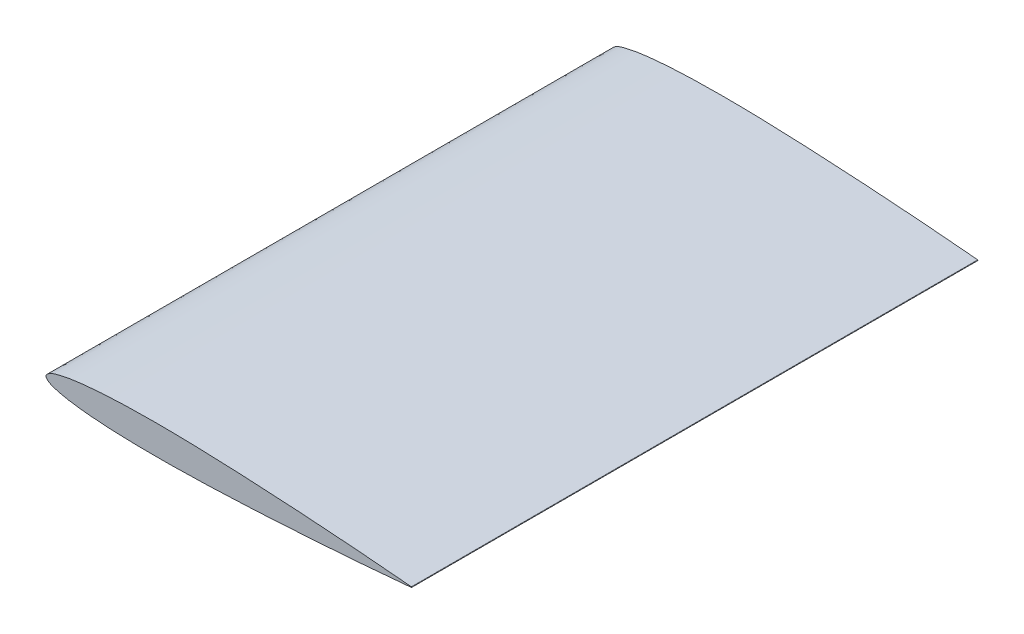
SolidWorks part; units mm, degrees
material "Manual Density from Real Component Stab Orizz. Ext Legno"
ref_plane "Piano frontale" through (0, 0, 0) normal (0, 0, 1) x (1, 0, 0)
ref_plane "Piano superiore" through (0, 0, 0) normal (0, 1, 0) x (1, 0, 0)
ref_plane "Piano destro" through (0, 0, 0) normal (1, 0, 0) x (0, 0, -1)
curve "Curva1"
  spline degree 3 poles (100, 0.084, 0) (98.3335, 0.2367, 0) (95.0012, 0.5422, 0) (88.3356, 1.1109, 0) (80.0033, 1.7636, 0) (70.003, 2.4579, 0) (60.0031, 3.0617, 0) (50.003, 3.5521, 0) (40.0026, 3.9029, 0) (31.667, 4.0253, 0) (24.9992, 3.9769, 0) (19.9978, 3.845, 0) (14.9934, 3.5925, 0) (10.8272, 3.2377, 0) (7.4891, 2.814, 0) (4.9936, 2.4037, 0) (2.8496, 1.8679, 0) (1.1654, 1.321, 0) (-0.6646, 0, 0) (1.1654, -1.321, 0) (2.8496, -1.8679, 0) (4.9936, -2.4037, 0) (7.4891, -2.814, 0) (10.8272, -3.2377, 0) (14.9934, -3.5925, 0) (19.9978, -3.845, 0) (24.9992, -3.9769, 0) (31.667, -4.0253, 0) (40.0026, -3.9029, 0) (50.003, -3.5521, 0) (60.0031, -3.0617, 0) (70.003, -2.4579, 0) (80.0033, -1.7636, 0) (88.3356, -1.1109, 0) (95.0012, -0.5422, 0) (98.3335, -0.2367, 0) (100, -0.084, 0) knots 0 0 0 0 0.024876 0.049742 0.099443 0.149112 0.198751 0.248359 0.297937 0.347491 0.372267 0.397051 0.421859 0.446731 0.45922 0.471791 0.48456 0.491195 0.5 0.508805 0.51544 0.528209 0.54078 0.553269 0.578141 0.602949 0.627733 0.652509 0.702063 0.751641 0.801249 0.850888 0.900557 0.950258 0.975124 1 1 1 1
sketch "Schizzo1" plane through (0, 0, 0) normal (0, 0, 1) x (1, 0, 0)
  line L0 (70, 2.443) -> (70, -2.443) construction
  arc A1 (70, -2.443) -> (70, 2.443) centre (70, 0) cw
  spline S0 degree 3 poles (905.2539, 3897.2705) (397.5402, -70.8596) (246.6176, -12.3941) (88.3356, 1.1109) (80.0033, 1.7636) (70.003, 2.4579) (60.0031, 3.0617) (50.003, 3.5521) (40.0026, 3.9029) (31.667, 4.0253) (24.9992, 3.9769) (19.9978, 3.845) (14.9934, 3.5925) (10.8272, 3.2377) (7.4891, 2.814) (4.9936, 2.4037) (2.8496, 1.8679) (1.1654, 1.321) (-0.6646, 0) (1.1654, -1.321) (2.8496, -1.8679) (4.9936, -2.4037) (7.4891, -2.814) (10.8272, -3.2377) (14.9934, -3.5925) (19.9978, -3.845) (24.9992, -3.9769) (31.667, -4.0253) (40.0026, -3.9029) (50.003, -3.5521) (60.0031, -3.0617) (70.003, -2.4579) (80.0033, -1.7636) (88.3356, -1.1109) (246.6156, 12.3939) (397.5363, 70.8581) (905.2338, -3897.1134) knots -2.261938 -2.261938 -2.261938 -2.261938 0.024876 0.049742 0.099443 0.149112 0.198751 0.248359 0.297937 0.347491 0.372267 0.397051 0.421859 0.446731 0.45922 0.471791 0.48456 0.491195 0.5 0.508805 0.51544 0.528209 0.54078 0.553269 0.578141 0.602949 0.627733 0.652509 0.702063 0.751641 0.801249 0.850888 0.900557 0.950258 0.975124 3.261907 3.261907 3.261907 3.261907 only from (100, 0.084) to (100, -0.084) construction
  spline S1 degree 3 poles (70, 2.443) (66.6677, 2.6593) (60.0031, 3.0617) (50.003, 3.5521) (40.0026, 3.9029) (31.667, 4.0253) (24.9992, 3.9769) (19.9978, 3.845) (14.9934, 3.5925) (10.8272, 3.2377) (7.4891, 2.814) (4.9936, 2.4037) (2.8496, 1.8679) (1.1654, 1.321) (-0.6646, 0) (1.1654, -1.321) (2.8496, -1.8679) (4.9936, -2.4037) (7.4891, -2.814) (10.8272, -3.2377) (14.9934, -3.5925) (19.9978, -3.845) (24.9992, -3.9769) (31.667, -4.0253) (40.0026, -3.9029) (50.003, -3.5521) (60.0031, -3.0617) (66.6677, -2.6593) (70, -2.443) knots 0.149112 0.149112 0.149112 0.149112 0.198751 0.248359 0.297937 0.347491 0.372267 0.397051 0.421859 0.446731 0.45922 0.471791 0.48456 0.491195 0.5 0.508805 0.51544 0.528209 0.54078 0.553269 0.578141 0.602949 0.627733 0.652509 0.702063 0.751641 0.801249 0.850888 0.850888 0.850888 0.850888
  dimension "D1" = 4.886
extrude "CorpoFoam" add sketch "Schizzo1" along normal blind 132
sketch "Schizzo7" plane through (0, 0, 132) normal (0, 0, 1) x (1, 0, 0)
  arc A0 (100, 0.084) -> (100, -0.084) centre (100, 0) cw
  spline S0 degree 3 poles (905.2539, 3897.2705) (397.5402, -70.8596) (246.6176, -12.3941) (88.3356, 1.1109) (80.0033, 1.7636) (70.003, 2.4579) (60.0031, 3.0617) (50.003, 3.5521) (40.0026, 3.9029) (31.667, 4.0253) (24.9992, 3.9769) (19.9978, 3.845) (14.9934, 3.5925) (10.8272, 3.2377) (7.4891, 2.814) (4.9936, 2.4037) (2.8496, 1.8679) (1.1654, 1.321) (-0.6646, 0) (1.1654, -1.321) (2.8496, -1.8679) (4.9936, -2.4037) (7.4891, -2.814) (10.8272, -3.2377) (14.9934, -3.5925) (19.9978, -3.845) (24.9992, -3.9769) (31.667, -4.0253) (40.0026, -3.9029) (50.003, -3.5521) (60.0031, -3.0617) (70.003, -2.4579) (80.0033, -1.7636) (88.3356, -1.1109) (246.6156, 12.3939) (397.5363, 70.8581) (905.2338, -3897.1134) knots -2.261938 -2.261938 -2.261938 -2.261938 0.024876 0.049742 0.099443 0.149112 0.198751 0.248359 0.297937 0.347491 0.372267 0.397051 0.421859 0.446731 0.45922 0.471791 0.48456 0.491195 0.5 0.508805 0.51544 0.528209 0.54078 0.553269 0.578141 0.602949 0.627733 0.652509 0.702063 0.751641 0.801249 0.850888 0.900557 0.950258 0.975124 3.261907 3.261907 3.261907 3.261907 only from (100, 0.084) to (100, -0.084) construction
  spline S1 degree 3 poles (100, 0.084) (98.3335, 0.2367) (95.0012, 0.5422) (88.3356, 1.1109) (80.0033, 1.7636) (70.003, 2.4579) (60.0031, 3.0617) (50.003, 3.5521) (40.0026, 3.9029) (31.667, 4.0253) (24.9992, 3.9769) (19.9978, 3.845) (14.9934, 3.5925) (10.8272, 3.2377) (7.4891, 2.814) (4.9936, 2.4037) (2.8496, 1.8679) (1.1654, 1.321) (-0.6646, 0) (1.1654, -1.321) (2.8496, -1.8679) (4.9936, -2.4037) (7.4891, -2.814) (10.8272, -3.2377) (14.9934, -3.5925) (19.9978, -3.845) (24.9992, -3.9769) (31.667, -4.0253) (40.0026, -3.9029) (50.003, -3.5521) (60.0031, -3.0617) (70.003, -2.4579) (80.0033, -1.7636) (88.3356, -1.1109) (95.0012, -0.5422) (98.3335, -0.2367) (100, -0.084) knots 0 0 0 0 0.024876 0.049742 0.099443 0.149112 0.198751 0.248359 0.297937 0.347491 0.372267 0.397051 0.421859 0.446731 0.45922 0.471791 0.48456 0.491195 0.5 0.508805 0.51544 0.528209 0.54078 0.553269 0.578141 0.602949 0.627733 0.652509 0.702063 0.751641 0.801249 0.850888 0.900557 0.950258 0.975124 1 1 1 1
extrude "FoamLaterale" add sketch "Schizzo7" along normal blind 23 and the other way through all
ref_plane "PianoBullone" through (0, 0, 6) normal (0, 0, -1) x (-1, 0, 0)
ref_plane "PianoIntagli" through (0, 10, 0) normal (0, 1, 0) x (1, 0, 0)
sketch "Schizzo8" plane through (0, 0, 0) normal (0, 0, -1) x (-1, 0, 0)
  line L1 (-15, 2) -> (-55, 2)
  line L2 (-15, 2) -> (-15, -2)
  line L3 (-15, -2) -> (-55, -2)
  line L4 (-55, 2) -> (-55, -2)
  line L5 (-15, 2) -> (-55, -2) construction
  line L6 (-15, -2) -> (-55, 2) construction
  point P0 (-35, 0)
  dimension "D1" = 4
  dimension "D2" = 40
  dimension "D3" = 15
extrude "TaglioSpina" cut sketch "Schizzo8" against normal blind 18
